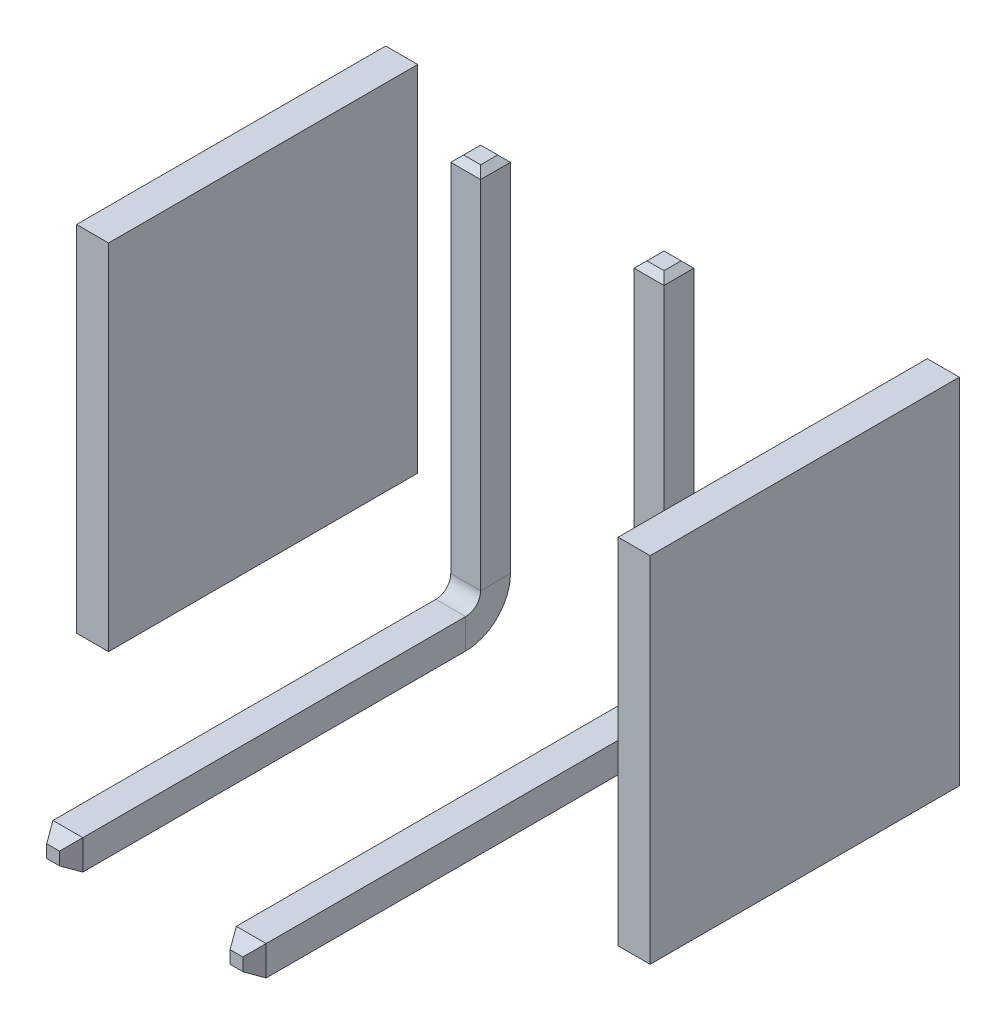
SolidWorks part; units mm, degrees
ref_plane "Front Plane" through (0, 0, 0) normal (0, 0, 1) x (1, 0, 0)
ref_plane "Top Plane" through (0, 0, 0) normal (0, 1, 0) x (1, 0, 0)
ref_plane "Right Plane" through (0, 0, 0) normal (1, 0, 0) x (0, 0, -1)
sketch "Sketch1" plane through (0, 0, 0) normal (0, 1, 0) x (1, 0, 0)
  line L0 (-0.9144, 0.1778) -> (0.9144, 0.1778) construction
  line L1 (-1.27, 0.1778) -> (-0.9144, 0.1778)
  line L2 (-1.27, 0.1778) -> (-1.27, -0.1778)
  line L3 (-1.27, -0.1778) -> (-0.9144, -0.1778)
  line L4 (-0.9144, 0.1778) -> (-0.9144, -0.1778)
  line L5 (0.9144, 0.1778) -> (1.27, 0.1778)
  line L6 (0.9144, 0.1778) -> (0.9144, -0.1778)
  line L7 (0.9144, -0.1778) -> (1.27, -0.1778)
  line L8 (1.27, 0.1778) -> (1.27, -0.1778)
  point P8 (0, 0.1778)
  point P10 (-0.9144, 0)
  point P11 (1.5887, -0.1778)
  dimension "D1" = 0.3556
  dimension "D2" = 2.54
sketch "Sketch2" plane through (0, 0, 0) normal (1, 0, 0) x (0, 0, -1)
  line L0 (-0.1778, 0) -> (-0.1778, -4.318)
  line L1 (-0.3556, -4.4958) -> (-5.0927, -4.4958)
  arc A0 (-0.1778, -4.318) -> (-0.3556, -4.4958) centre (-0.3556, -4.318) cw
  dimension "D2" = 0.1778
  dimension "D1" = 4.318
  dimension "D3" = 4.9149
sweep "Sweep1" add profiles "Sketch1" path "Sketch2"
sketch "Sketch4" plane through (0, -4.8514, 0) normal (0, -1, 0) x (1, 0, 0)
  line L0 (1.27, 0.3556) -> (1.27, 5.0927) construction
  line L1 (3.4163, 2.4892) -> (3.0353, 2.4892)
  line L2 (3.4163, 2.4892) -> (3.4163, -1.1938)
  line L3 (3.4163, -1.1938) -> (3.0353, -1.1938)
  line L4 (3.0353, 2.4892) -> (3.0353, -1.1938)
  line L5 (1.27, -0.1778) -> (0.9144, -0.1778) construction
  line L6 (0, -1.1938) -> (0, 2.4892) construction
  line L7 (-3.0353, 2.4892) -> (-3.0353, -1.1938)
  line L8 (-3.4163, -1.1938) -> (-3.0353, -1.1938)
  line L9 (-3.4163, 2.4892) -> (-3.4163, -1.1938)
  line L10 (-3.4163, 2.4892) -> (-3.0353, 2.4892)
  point P10 (3.4163, 0.6477)
  point P11 (0, 0.6477)
  dimension "D1" = 1.7653
  dimension "D2" = 0.381
  dimension "D3" = 1.016
  dimension "D4" = 3.683
extrude "Boss-Extrude1" add sketch "Sketch4" against normal blind 4.2164 separate body
chamfer "Chamfer1" distance 0.0762 angle 45 4 edges at (1.0922, 0, -0.1778) (1.27, 0, 0) (1.0922, 0, 0.1778) (0.9144, 0, 0)
chamfer "Chamfer2" distance 0.0762 angle 45 4 edges at (-1.0922, 0, -0.1778) (-0.9144, 0, 0) (-1.0922, 0, 0.1778) (-1.27, 0, 0)
chamfer "Chamfer3" distance 0.1016 angle 60 4 edges at (-1.0922, -4.4958, 5.0927) (-0.9144, -4.6736, 5.0927) (-1.0922, -4.8514, 5.0927) (-1.27, -4.6736, 5.0927)
chamfer "Chamfer4" distance 0.1016 angle 60 4 edges at (1.0922, -4.4958, 5.0927) (1.27, -4.6736, 5.0927) (1.0922, -4.8514, 5.0927) (0.9144, -4.6736, 5.0927)
